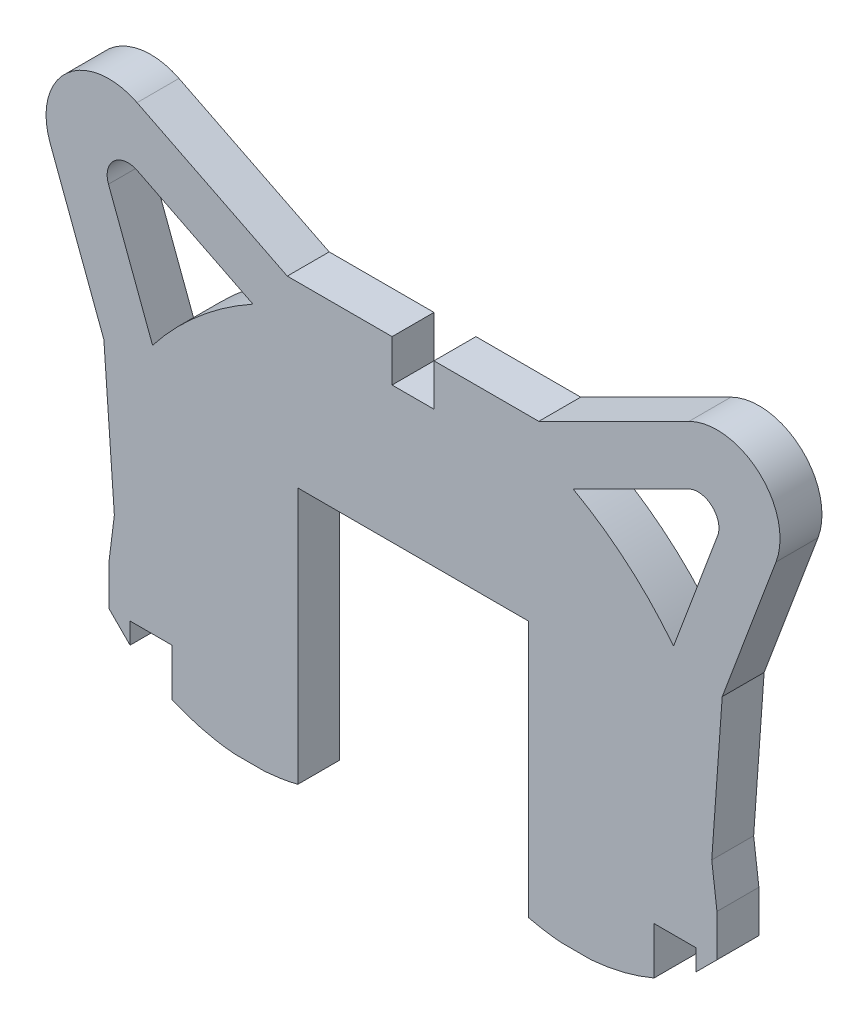
SolidWorks part; units mm, degrees
ref_plane "Piano frontale" through (0, 0, 0) normal (0, 0, 1) x (1, 0, 0)
ref_plane "Piano superiore" through (0, 0, 0) normal (0, 1, 0) x (1, 0, 0)
ref_plane "Piano destro" through (0, 0, 0) normal (1, 0, 0) x (0, 0, -1)
sketch "Schizzo1" plane through (0, 0, 0) normal (0, 0, 1) x (1, 0, 0)
  line L0 (-2, -11) -> (2, -11)
  line L1 (-2, -11) -> (-2, -7)
  line L2 (-12, -7) -> (-26.3339, 0.1669)
  line L3 (-2, -7) -> (-12, -7)
  line L4 (-34.6351, -7.3064) -> (-29.5, -21)
  line L6 (-29, -43) -> (-27, -45)
  line L7 (-27, -45) -> (-27, -43)
  line L8 (-27, -43) -> (-23, -43)
  line L9 (-23, -43) -> (-23, -49)
  line L10 (-23, -49) -> (-11, -49)
  line L11 (-11, -49) -> (-11, -24)
  line L12 (-11, -24) -> (11, -24)
  line L14 (11, -49) -> (11, -24)
  line L15 (23, -49) -> (11, -49)
  line L16 (23, -43) -> (23, -49)
  line L17 (27, -43) -> (23, -43)
  line L18 (27, -45) -> (27, -43)
  line L19 (29, -43) -> (27, -45)
  line L21 (34.6351, -7.3064) -> (29.5, -21)
  line L22 (2, -7) -> (12, -7)
  line L23 (12, -7) -> (26.3339, 0.1669)
  line L24 (2, -11) -> (2, -7)
  line L25 (-2, -7) -> (2, -7)
  line L26 (-24.2883, -20.6578) -> (-29.0593, -7.9352)
  line L27 (-26.2922, -5.4441) -> (-13.3561, -11.9121)
  line L28 (-13.3561, -11.9121) -> (-24.2883, -20.6578)
  line L29 (13.3561, -11.9121) -> (26.2922, -5.4441)
  line L30 (29.0593, -7.9352) -> (24.2883, -20.6578)
  line L31 (24.2883, -20.6578) -> (13.3561, -11.9121)
  line L32 (-12, -7) -> (-29.5, -21)
  line L33 (12, -7) -> (29.5, -21)
  line L34 (-29.5, -21) -> (-28.5, -35)
  line L35 (-28.5, -35) -> (-29, -39)
  line L36 (-29, -39) -> (-29, -43)
  line L37 (29.5, -21) -> (28.5, -35)
  line L38 (28.5, -35) -> (29, -39)
  line L39 (29, -39) -> (29, -43)
  circle A0 centre (0, -38.5) radius 31.5
  arc A1 (26.3339, 0.1669) -> (34.6351, -7.3064) centre (29.0171, -5.1996) cw
  arc A2 (26.2922, -5.4441) -> (29.0593, -7.9352) centre (27.1867, -7.2329) cw
  arc A3 (-34.6351, -7.3064) -> (-26.3339, 0.1669) centre (-29.0171, -5.1996) cw
  arc A4 (-26.2922, -5.4441) -> (-29.0593, -7.9352) centre (-27.1867, -7.2329) ccw
  spline S0 degree 2 poles (-23, -47.5) (-17.1611, -49.9869) (-11, -48.5) knots 0 0 0 1 1 1
  spline S1 degree 2 poles (11, -48.5) (17.1611, -49.9869) (23, -47.5) knots 0 0 0 1 1 1
  point P4 (0, -11)
  point P28 (0, 1)
  point P35 (-19.8242, -8.6781)
  point P46 (40, 7)
  point P53 (-40, 7)
  dimension "D31" = 63
  dimension "D48" = 6
  dimension "D49" = 2
  dimension "D50" = 6
  dimension "D51" = 2
  dimension "D2" = 4
  dimension "D3" = 4
  dimension "D4" = 25
  dimension "D5" = 4
  dimension "D6" = 10
  dimension "D7" = 2
  dimension "D8" = 2
  dimension "D9" = 6
  dimension "D10" = 12
  dimension "D11" = 28
  dimension "D12" = 28
  dimension "D13" = 28
  dimension "D14" = 22
  dimension "D15" = 0.5
  dimension "D16" = 10
  dimension "D17" = 4
  dimension "D18" = 10.5
  dimension "D19" = 28
  dimension "D20" = 14
  dimension "D21" = 14
  dimension "D22" = 22
  dimension "D23" = 0.5
  dimension "D24" = 4
  dimension "D25" = 12
  dimension "D26" = 10.5
  dimension "D27" = 2
  dimension "D28" = 2
  dimension "D29" = 6
  dimension "D30" = 25
  dimension "D32" = 5
  dimension "D33" = 5
  dimension "D34" = 5
  dimension "D35" = 5
  dimension "D36" = 14
  dimension "D37" = 14
  dimension "D38" = 1.5
  dimension "D39" = 0.5
  dimension "D40" = 0.5
  dimension "D41" = 14
  dimension "D42" = 14
  dimension "D43" = 4
  dimension "D44" = 1
  dimension "D45" = 1
  dimension "D46" = 4
  dimension "D47" = 0.5
extrude "Estrusione-Estrusione1" add sketch "Schizzo1" along normal blind 4 contours L14 S1 L15 L16 L17 L18 L19 A0 L39 L38 L37 L24 L0 L1 L34 L35 L36 L6 L7 L8 L9 S0 L10 L11 L12 | A0 L1 L3 L32 L34 | A0 L37 L33 L22 L24 | L23 L33 L21 L30 L31 L29 | L32 L2 L4 L27 L28 L26 | A0 L26 L32 L34 | L27 A0 L26 L28 | L30 A0 L29 L31 | A0 L37 L33 L30
